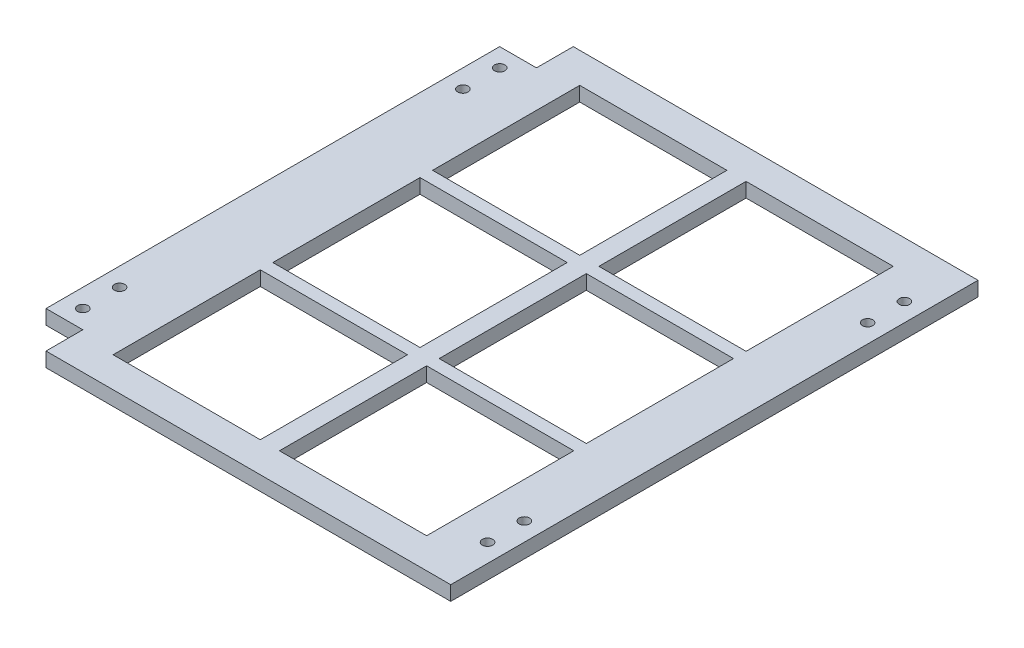
SolidWorks part; units mm, degrees
ref_plane "前视" through (0, 0, 0) normal (0, 0, 1) x (1, 0, 0)
ref_plane "上视" through (0, 0, 0) normal (0, 1, 0) x (1, 0, 0)
ref_plane "右视" through (0, 0, 0) normal (1, 0, 0) x (0, 0, -1)
sketch "Sketch1" plane through (0, 0, 0) normal (0, 1, 0) x (1, 0, 0)
  line L1 (-139.7, 182) -> (139.7, 182)
  line L2 (-139.7, 182) -> (-139.7, -182)
  line L3 (-139.7, -182) -> (139.7, -182)
  line L4 (139.7, 182) -> (139.7, -182)
  point P4 (-127, -170.8875)
  point P7 (76.2, -169.7275)
  point P8 (76.2, 170.8875)
  point P9 (-127, 170.8875)
  point P17 (-101.6, -170.8875)
  point P18 (-101.6, 170.8875)
  point P23 (101.6, -169.7275)
  point P24 (101.6, 170.8875)
  dimension "D5" = 63.5
  dimension "D7" = 203.2033
  dimension "D16" = 25.4
  dimension "D1" = 279.4
  dimension "D2" = 364
  dimension "D3" = 11.1125
  dimension "D4" = 12.7
  dimension "D6" = 11.1125
  dimension "D8" = 63.5
  dimension "D9" = 11.1125
  dimension "D10" = 12.7
  dimension "D11" = 182
  dimension "D12" = 139.7
  dimension "D13" = 25.4
  dimension "D15" = 25.4
  dimension "D17" = 25.4
extrude "Boss-Extrude1" add sketch "Sketch1" along normal blind 10
sketch "Sketch2" plane through (0, 10, 0) normal (0, 1, 0) x (1, 0, 0)
  line L0 (-114.3, 50.8) -> (-12.7, 50.8)
  line L1 (-114.3, 50.8) -> (-114.3, -50.8)
  line L2 (-12.7, 50.8) -> (-12.7, -50.8)
  line L3 (-114.3, -50.8) -> (-12.7, -50.8)
  line L4 (-114.3, 50.8) -> (-12.7, -50.8) construction
  line L5 (-12.7, 50.8) -> (-114.3, -50.8) construction
  line L6 (-139.7, 182) -> (-139.7, -182) construction
  point P1 (-63.5, 0)
  dimension "D4" = 0
  dimension "D3" = 76.2
  dimension "D1" = 101.6
  dimension "D2" = 101.6
extrude "Cut-Extrude1" cut sketch "Sketch2" against normal through all
pattern_linear "LPattern1" count 2 spacing 110.265 along (0, 0, -1) of "Cut-Extrude1"
pattern_linear "LPattern2" count 2 spacing 110.265 along (0, 0, 1) of "Cut-Extrude1"
pattern_linear "LPattern3" count 2 spacing 114.82 along (1, 0, 0) of "Cut-Extrude1", "LPattern1", "LPattern2"
sketch "Sketch3" plane through (-139.7, 0, 0) normal (-1, 0, 0) x (0, 0, 1)
  line L0 (-182, 0) -> (182, 0) construction
  line L1 (-156.58, 0) -> (156.58, 0)
  line L2 (-156.58, 0) -> (-156.58, 10)
  line L3 (-156.58, 10) -> (156.58, 10)
  line L4 (156.58, 0) -> (156.58, 10)
  line L5 (-182, 10) -> (182, 10) construction
  line L6 (182, 10) -> (182, 0) construction
  line L7 (-182, 10) -> (-182, 0) construction
  dimension "D1" = 25.42
  dimension "D2" = 25.42
extrude "Boss-Extrude2" add sketch "Sketch3" along normal blind 25.4
sketch "Sketch4" plane through (0, 0, 0) normal (0, -1, 0) x (1, 0, 0)
  line L0 (139.7, 182) -> (139.7, -182) construction
  line L1 (139.7, -182) -> (-139.7, -182) construction
  line L2 (139.7, 182) -> (139.7, -182) construction
  line L3 (-165.1, 156.58) -> (-165.1, -156.58) construction
  line L4 (139.7, -182) -> (-139.7, -182) construction
  circle A6 centre (127.0013, -118.5053) radius 3.5687
  circle A7 centre (127.0013, -143.9053) radius 3.5687
  circle A14 centre (-152.4, -118.5053) radius 3.5687
  circle A15 centre (-152.4, -143.9053) radius 3.5687
  dimension "D2" = 38.0947
  dimension "D3" = 7.1374
  dimension "D4" = 25.4
  dimension "D5" = 7.1374
  dimension "D6" = 12.6987
  dimension "D7" = 12.7
  dimension "D8" = 7.1374
  dimension "D9" = 38.0947
  dimension "D10" = 25.4
  dimension "D11" = 7.1374
  dimension "D12" = 12.7
  dimension "D1" = 12.6987
extrude "Cut-Extrude2" cut sketch "Sketch4" against normal blind 10
mirror "Mirror1" about plane through (0, 0, 0) normal (0, 0, 1) of "Cut-Extrude2"
